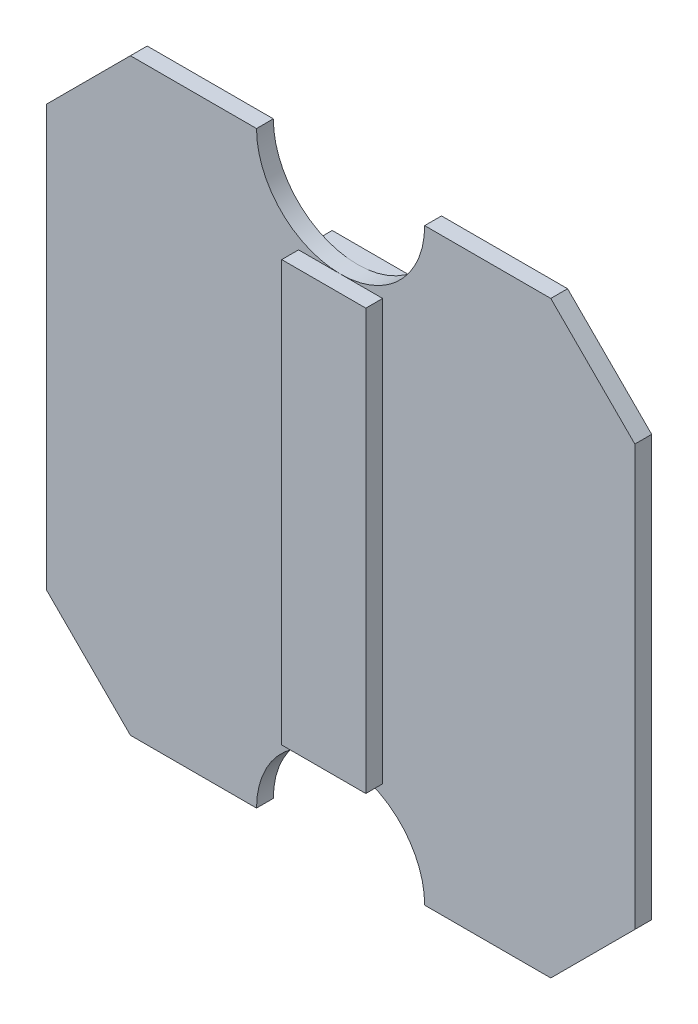
SolidWorks part; units mm, degrees
ref_plane "Front Plane" through (0, 0, 0) normal (0, 0, 1) x (1, 0, 0)
ref_plane "Top Plane" through (0, 0, 0) normal (0, 1, 0) x (1, 0, 0)
ref_plane "Right Plane" through (0, 0, 0) normal (1, 0, 0) x (0, 0, -1)
sketch "Sketch1" plane through (0, 0, 0) normal (0, 0, 1) x (1, 0, 0)
  line L0 (0, 0) -> (0, 331.6532) construction
  line L1 (-125, 175) -> (-50, 175)
  line L2 (-175, 125) -> (-175, -125)
  line L3 (-125, -175) -> (-50, -175)
  line L4 (175, 125) -> (175, -125)
  line L5 (50, -175) -> (125, -175)
  line L6 (50, 175) -> (125, 175)
  line L9 (0, 0) -> (347.1774, 0) construction
  line L10 (125, 175) -> (175, 125)
  line L11 (125, -175) -> (175, -125)
  line L12 (-125, -175) -> (-175, -125)
  line L13 (-125, 175) -> (-175, 125)
  arc A0 (-50, 175) -> (50, 175) centre (0, 175) ccw
  arc A1 (50, -175) -> (-50, -175) centre (0, -175) ccw
  dimension "D7" = 100
  dimension "D8" = 100
  dimension "D1" = 175
  dimension "D2" = 175
  dimension "D3" = 175
  dimension "D4" = 175
  dimension "D5" = 50
  dimension "D6" = 50
  dimension "D9" = 75
  dimension "D10" = 75
extrude "Boss-Extrude1" add sketch "Sketch1" along normal blind 10
sketch "Sketch2" plane through (0, 0, 10) normal (0, 0, 1) x (1, 0, 0)
  line L0 (0, -200000) -> (0, 200331.6532) construction
  line L3 (-2.1489, 125) -> (-25, 125)
  line L4 (-25, 0) -> (-25, 125)
  line L5 (-25, 125) -> (25, 125)
  line L6 (-25, 125) -> (-25, -125)
  line L7 (-25, -125) -> (25, -125)
  line L8 (25, 125) -> (25, -125)
  arc A0 (-50, 175) -> (50, 175) centre (0, 175) ccw construction
  arc A1 (50, -175) -> (-50, -175) centre (0, -175) ccw construction
  point P12 (0, 125)
  point P16 (0, -125)
  dimension "D1" = 25
  dimension "D2" = 25
extrude "Boss-Extrude2" add sketch "Sketch2" along normal blind 10 and the other way blind 20 contours L8 L5 L3 L4 L6 L7
